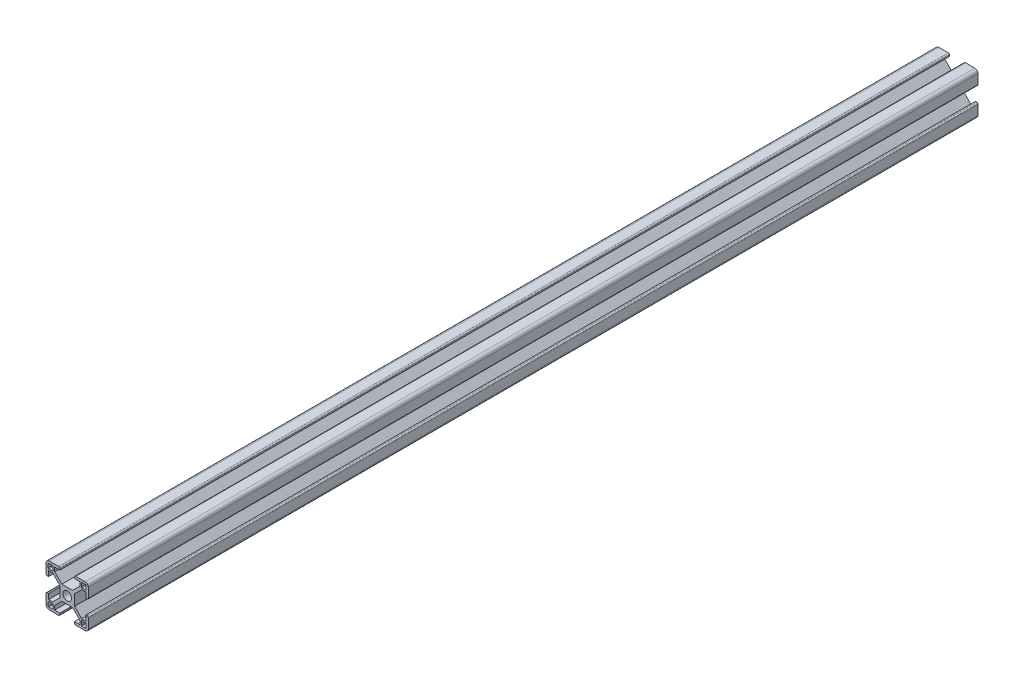
SolidWorks part; units mm, degrees
ref_plane "Alzado" through (0, 0, 0) normal (0, 0, 1) x (1, 0, 0)
ref_plane "Planta" through (0, 0, 0) normal (0, 1, 0) x (1, 0, 0)
ref_plane "Vista lateral" through (0, 0, 0) normal (1, 0, 0) x (0, 0, -1)
sketch "Croquis1" plane through (0, 0, 0) normal (0, 0, 1) x (1, 0, 0)
  line L0 (-5.8, 0) -> (5.8, 0) construction
  line L1 (5.8, -4.24) -> (5.8, 4.24)
  line L2 (5.8, 4.24) -> (11.47, 9.91)
  line L3 (11.47, 9.91) -> (14.66, 9.91)
  line L4 (14.66, 9.91) -> (14.66, 5.73)
  line L5 (14.66, 5.73) -> (15.66, 5.73)
  line L6 (16.66, 6.73) -> (16.66, 14.16)
  line L7 (0, 0) -> (16.66, 16.66) construction
  line L8 (5.73, 14.66) -> (5.73, 15.66)
  line L9 (6.73, 16.66) -> (14.16, 16.66)
  line L10 (9.91, 14.66) -> (5.73, 14.66)
  line L11 (9.91, 11.47) -> (9.91, 14.66)
  line L12 (4.24, 5.8) -> (9.91, 11.47)
  line L13 (-4.24, 5.8) -> (4.24, 5.8)
  line L14 (0, 5.8) -> (0, -5.8) construction
  line L15 (11.6515, 14.9015) -> (14.4015, 14.9015)
  line L16 (11.1515, 14.4015) -> (11.1515, 11.6515)
  line L17 (11.6515, 11.1515) -> (14.4015, 11.1515)
  line L18 (14.9015, 14.4015) -> (14.9015, 11.6515)
  line L19 (11.1515, 14.9015) -> (14.9015, 11.1515) construction
  line L20 (11.1515, 11.1515) -> (14.9015, 14.9015) construction
  line L21 (-11.1515, 11.1515) -> (-14.9015, 14.9015) construction
  line L22 (-11.1515, 14.9015) -> (-14.9015, 11.1515) construction
  line L23 (0, 0) -> (-16.66, 16.66) construction
  line L24 (-14.9015, 14.4015) -> (-14.9015, 11.6515)
  line L25 (-11.6515, 11.1515) -> (-14.4015, 11.1515)
  line L26 (-11.1515, 14.4015) -> (-11.1515, 11.6515)
  line L27 (-11.6515, 14.9015) -> (-14.4015, 14.9015)
  line L28 (-4.24, 5.8) -> (-9.91, 11.47)
  line L29 (-9.91, 11.47) -> (-9.91, 14.66)
  line L30 (-9.91, 14.66) -> (-5.73, 14.66)
  line L31 (-6.73, 16.66) -> (-14.16, 16.66)
  line L32 (-5.73, 14.66) -> (-5.73, 15.66)
  line L33 (-16.66, 6.73) -> (-16.66, 14.16)
  line L34 (-14.66, 5.73) -> (-15.66, 5.73)
  line L35 (-14.66, 9.91) -> (-14.66, 5.73)
  line L36 (-11.47, 9.91) -> (-14.66, 9.91)
  line L37 (-5.8, 4.24) -> (-11.47, 9.91)
  line L38 (-5.8, -4.24) -> (-5.8, 4.24)
  line L39 (0, 0) -> (-16.66, -16.66) construction
  line L40 (-11.1515, -14.9015) -> (-14.9015, -11.1515) construction
  line L41 (-11.1515, -11.1515) -> (-14.9015, -14.9015) construction
  line L42 (11.1515, -11.1515) -> (14.9015, -14.9015) construction
  line L43 (11.1515, -14.9015) -> (14.9015, -11.1515) construction
  line L44 (0, 0) -> (16.66, -16.66) construction
  line L45 (-5.8, -4.24) -> (-11.47, -9.91)
  line L46 (-11.47, -9.91) -> (-14.66, -9.91)
  line L47 (-14.66, -9.91) -> (-14.66, -5.73)
  line L48 (-14.66, -5.73) -> (-15.66, -5.73)
  line L49 (-16.66, -6.73) -> (-16.66, -14.16)
  line L50 (-5.73, -14.66) -> (-5.73, -15.66)
  line L51 (-6.73, -16.66) -> (-14.16, -16.66)
  line L52 (-9.91, -14.66) -> (-5.73, -14.66)
  line L53 (-9.91, -11.47) -> (-9.91, -14.66)
  line L54 (-4.24, -5.8) -> (-9.91, -11.47)
  line L55 (-11.6515, -14.9015) -> (-14.4015, -14.9015)
  line L56 (-11.1515, -14.4015) -> (-11.1515, -11.6515)
  line L57 (-11.6515, -11.1515) -> (-14.4015, -11.1515)
  line L58 (-14.9015, -14.4015) -> (-14.9015, -11.6515)
  line L59 (14.9015, -14.4015) -> (14.9015, -11.6515)
  line L60 (11.6515, -11.1515) -> (14.4015, -11.1515)
  line L61 (11.1515, -14.4015) -> (11.1515, -11.6515)
  line L62 (11.6515, -14.9015) -> (14.4015, -14.9015)
  line L63 (-4.24, -5.8) -> (4.24, -5.8)
  line L64 (4.24, -5.8) -> (9.91, -11.47)
  line L65 (9.91, -11.47) -> (9.91, -14.66)
  line L66 (9.91, -14.66) -> (5.73, -14.66)
  line L67 (6.73, -16.66) -> (14.16, -16.66)
  line L68 (5.73, -14.66) -> (5.73, -15.66)
  line L69 (16.66, -6.73) -> (16.66, -14.16)
  line L70 (14.66, -5.73) -> (15.66, -5.73)
  line L71 (14.66, -9.91) -> (14.66, -5.73)
  line L72 (11.47, -9.91) -> (14.66, -9.91)
  line L73 (5.8, -4.24) -> (11.47, -9.91)
  arc A0 (15.66, 5.73) -> (16.66, 6.73) centre (15.66, 6.73) ccw
  arc A1 (16.66, 14.16) -> (14.16, 16.66) centre (14.16, 14.16) ccw
  arc A2 (5.73, 15.66) -> (6.73, 16.66) centre (6.73, 15.66) cw
  arc A3 (11.1515, 11.6515) -> (11.6515, 11.1515) centre (11.6515, 11.6515) ccw
  arc A4 (14.4015, 11.1515) -> (14.9015, 11.6515) centre (14.4015, 11.6515) ccw
  arc A5 (14.4015, 14.9015) -> (14.9015, 14.4015) centre (14.4015, 14.4015) cw
  arc A6 (11.6515, 14.9015) -> (11.1515, 14.4015) centre (11.6515, 14.4015) ccw
  arc A7 (-11.6515, 14.9015) -> (-11.1515, 14.4015) centre (-11.6515, 14.4015) cw
  arc A8 (-14.4015, 14.9015) -> (-14.9015, 14.4015) centre (-14.4015, 14.4015) ccw
  arc A9 (-14.4015, 11.1515) -> (-14.9015, 11.6515) centre (-14.4015, 11.6515) cw
  arc A10 (-11.1515, 11.6515) -> (-11.6515, 11.1515) centre (-11.6515, 11.6515) cw
  arc A11 (-5.73, 15.66) -> (-6.73, 16.66) centre (-6.73, 15.66) ccw
  arc A12 (-16.66, 14.16) -> (-14.16, 16.66) centre (-14.16, 14.16) cw
  arc A13 (-15.66, 5.73) -> (-16.66, 6.73) centre (-15.66, 6.73) cw
  arc A14 (-15.66, -5.73) -> (-16.66, -6.73) centre (-15.66, -6.73) ccw
  arc A15 (-16.66, -14.16) -> (-14.16, -16.66) centre (-14.16, -14.16) ccw
  arc A16 (-5.73, -15.66) -> (-6.73, -16.66) centre (-6.73, -15.66) cw
  arc A17 (-11.1515, -11.6515) -> (-11.6515, -11.1515) centre (-11.6515, -11.6515) ccw
  arc A18 (-14.4015, -11.1515) -> (-14.9015, -11.6515) centre (-14.4015, -11.6515) ccw
  arc A19 (-14.4015, -14.9015) -> (-14.9015, -14.4015) centre (-14.4015, -14.4015) cw
  arc A20 (-11.6515, -14.9015) -> (-11.1515, -14.4015) centre (-11.6515, -14.4015) ccw
  arc A21 (11.6515, -14.9015) -> (11.1515, -14.4015) centre (11.6515, -14.4015) cw
  arc A22 (14.4015, -14.9015) -> (14.9015, -14.4015) centre (14.4015, -14.4015) ccw
  arc A23 (14.4015, -11.1515) -> (14.9015, -11.6515) centre (14.4015, -11.6515) cw
  arc A24 (11.1515, -11.6515) -> (11.6515, -11.1515) centre (11.6515, -11.6515) cw
  arc A25 (5.73, -15.66) -> (6.73, -16.66) centre (6.73, -15.66) ccw
  arc A26 (16.66, -14.16) -> (14.16, -16.66) centre (14.16, -14.16) cw
  arc A27 (15.66, -5.73) -> (16.66, -6.73) centre (15.66, -6.73) cw
  circle A28 centre (0, 0) radius 3.4
  point P17 (16.66, 5.73)
  point P23 (5.73, 16.66)
  point P24 (13.0265, 13.0265)
  point P76 (-13.0265, 13.0265)
  point P77 (-5.73, 16.66)
  point P78 (-16.66, 5.73)
  point P148 (-16.66, -5.73)
  point P149 (-5.73, -16.66)
  point P150 (-13.0265, -13.0265)
  point P151 (13.0265, -13.0265)
  point P152 (5.73, -16.66)
  point P153 (16.66, -5.73)
  dimension "D9" = 1
  dimension "D10" = 2.5
  dimension "D11" = 1
  dimension "D14" = 0.5
  dimension "D15" = 6.8
  dimension "D2" = 4.24
  dimension "D3" = 135
  dimension "D4" = 5.67
  dimension "D5" = 3.19
  dimension "D6" = 4.18
  dimension "D7" = 10.93
  dimension "D8" = 2
  dimension "D12" = 3.75
  dimension "D13" = 3.75
extrude "Saliente-Extruir3" add sketch "Croquis1" along normal blind 700
sketch "Croquis2" plane through (0, 0, 700) normal (0, 0, 1) x (1, 0, 0)
  line L0 (-16.66, -14.16) -> (16.66, -14.16)
